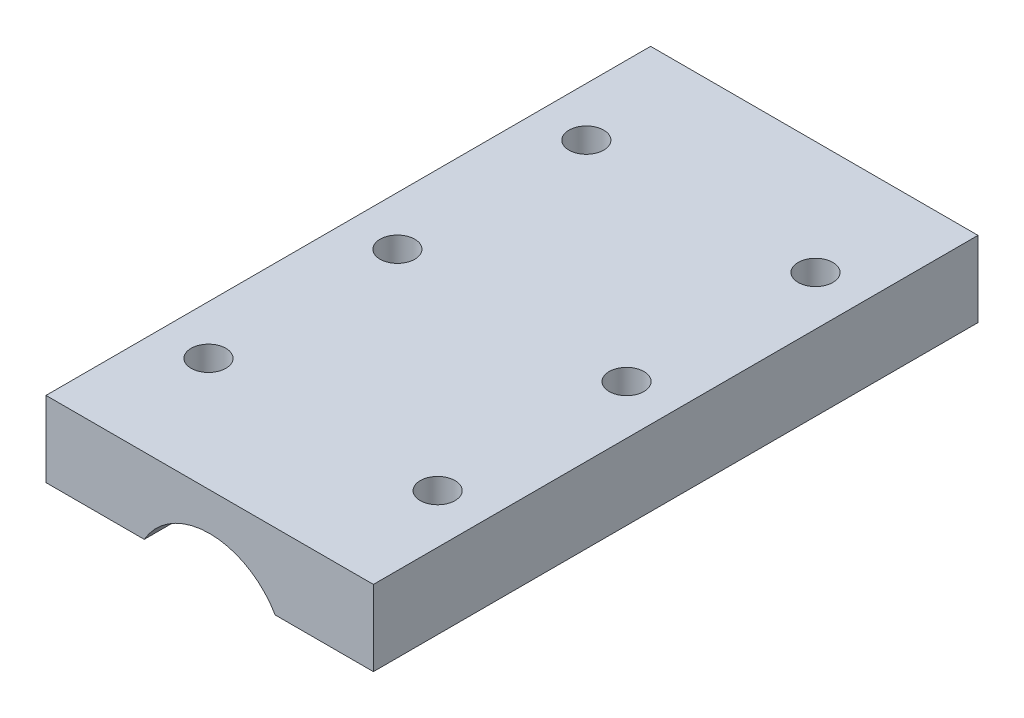
SolidWorks part; units mm, degrees
material "PETG"
ref_plane "Спереди" through (0, 0, 0) normal (0, 0, 1) x (1, 0, 0)
ref_plane "Сверху" through (0, 0, 0) normal (0, 1, 0) x (1, 0, 0)
ref_plane "Справа" through (0, 0, 0) normal (1, 0, 0) x (0, 0, -1)
sketch "Эскиз1" plane through (0, 0, 0) normal (0, 1, 0) x (1, 0, 0)
  line L1 (10.8301, 20) -> (-10.8301, 20)
  line L2 (10.8301, 20) -> (10.8301, -20)
  line L3 (10.8301, -20) -> (-10.8301, -20)
  line L4 (-10.8301, 20) -> (-10.8301, -20)
  line L5 (10.8301, 20) -> (-10.8301, -20) construction
  line L6 (10.8301, -20) -> (-10.8301, 20) construction
  point P0 (0, 0)
  dimension "D1" = 21.6603
  dimension "D2" = 40
extrude "Бобышка-Вытянуть1" add sketch "Эскиз1" along normal blind 5
sketch "Эскиз2" plane through (0, 0, 20) normal (0, 0, 1) x (1, 0, 0)
  line L0 (-10.8301, 0) -> (10.8301, 0) construction
  line L1 (0, 0) -> (0, -50000) construction
  line L2 (-4.3301, 0) -> (4.3301, 0)
  arc A0 (-4.3301, 0) -> (4.3301, 0) centre (0, -2.5) cw
  point P7 (0, 0)
  dimension "D1" = 5
  dimension "D2" = 6.5
extrude "Вырез-Вытянуть1" cut sketch "Эскиз2" against normal up to surface (40 mm away) up to face at (0, 2.5, -20)
sketch "Эскиз3" plane through (0, 0, 0) normal (0, -1, 0) x (1, 0, 0)
  line L0 (0, 0) -> (0, 50000) construction
  line L1 (0, 0) -> (50000, 0) construction
  line L2 (7.5801, 20) -> (7.5801, -20) construction
  line L3 (4.3301, 20) -> (10.8301, 20) construction
  line L4 (10.8301, -20) -> (4.3301, -20) construction
  circle A0 centre (7.5801, 12.5) radius 1.15
  circle A1 centre (7.5801, -12.5) radius 1.15
  circle A2 centre (7.5801, 0) radius 1.15
  circle A3 centre (-7.5801, -12.5) radius 1.15
  circle A4 centre (-7.5801, 0) radius 1.15
  circle A5 centre (-7.5801, 12.5) radius 1.15
  point P17 (0, 0)
  dimension "D1" = 2.3
  dimension "D2" = 7.5
extrude "Вырез-Вытянуть2" cut sketch "Эскиз3" against normal up to surface (5 mm away) up to face at (0, 5, 0)
